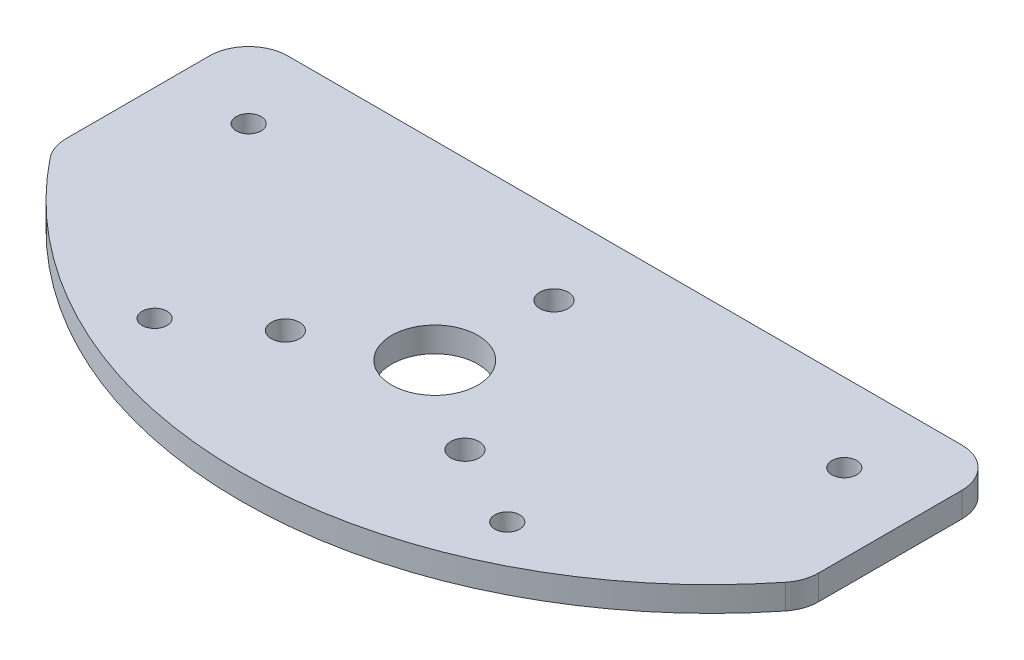
SolidWorks part; units mm, degrees
other "Markup1"
sketch "Sketch11" plane through (96, 6.36, -96) normal (0.0924, 0.995, -0.0379) x (0.9957, -0.0926, -0.0033)
ref_plane "Front Plane" through (0, 0, 0) normal (0, 0, 1) x (1, 0, 0)
ref_plane "Top Plane" through (0, 0, 0) normal (0, 1, 0) x (1, 0, 0)
ref_plane "Right Plane" through (0, 0, 0) normal (1, 0, 0) x (0, 0, -1)
sketch "Construction geometry" plane through (0, 0, 0) normal (0, 1, 0) x (1, 0, 0)
  line L1 (-96, 96) -> (96, 96)
  line L2 (-96, 96) -> (-96, -96)
  line L3 (-96, -96) -> (96, -96)
  line L4 (96, 96) -> (96, -96)
  line L5 (0, 96) -> (0, -96)
  line L6 (-96, 0) -> (96, 0)
  point P8 (0, 0)
  dimension "D1" = 192
  dimension "D2" = 192
sketch "Sketch5" plane through (0, 0, 0) normal (0, 1, 0) x (1, 0, 0)
  line L0 (-96, 0) -> (96, 0) construction
  line L1 (0, 96) -> (0, -96) construction
  circle A0 centre (0, 0) radius 38.5
  dimension "D1" = 77
extrude "Boss-Extrude2" add sketch "Sketch5" along normal blind 6.36
sketch "Sketch7" plane through (0, 6.36, 0) normal (0, 1, 0) x (1, 0, 0)
  line L0 (0, 96) -> (0, -96) construction
  line L1 (-96, 0) -> (96, 0) construction
  circle A0 centre (0, 0) radius 30 construction
  circle A1 centre (0, 30) radius 3.625
  circle A6 centre (25.9808, -15) radius 3.625
  circle A7 centre (-25.9808, -15) radius 3.625
  point P24 (0, 0)
  dimension "D2" = 60
  dimension "D1" = 7.25
  dimension "D4" = 3
extrude "Cut-Extrude3" [suppressed] cut sketch "Sketch7" against normal through all
sketch "Sketch8" plane through (0, 6.36, 0) normal (0, 1, 0) x (1, 0, 0)
  line L1 (-96, 0) -> (96, 0) construction
  circle A0 centre (0, 0) radius 11
  dimension "D1" = 22
extrude "Cut-Extrude4" cut sketch "Sketch8" against normal through all
sketch "Sketch9" plane through (0, 6.36, 0) normal (0, 1, 0) x (1, 0, 0)
  line L5 (-96, 48.5) -> (96, 48.5)
  line L6 (-96, 96) -> (-96, -96) construction
  line L7 (96, 96) -> (96, -96) construction
  line L8 (96, 48.5) -> (96, -1.5)
  line L9 (-96, 48.5) -> (-96, -1.5)
  line L10 (0, 96) -> (0, -96) construction
  circle A0 centre (0, 0) radius 38.5
  circle A3 centre (0, 0) radius 38.5 construction
  arc A4 (96, -1.5) -> (-96, -1.5) centre (0, 70.5) cw
  point P13 (0, -49.5)
  dimension "D1" = 120
  dimension "D2" = 50
  dimension "D3" = 10
extrude "Boss-Extrude3" add sketch "Sketch9" against normal up to surface (6.36 mm away) up to face at (0, 0, 11)
sketch "Sketch10" plane through (0, 6.36, 0) normal (0, 1, 0) x (1, 0, 0)
  line L0 (0, 48.5) -> (0, -49.5) construction
  line L1 (96, 48.5) -> (-96, 48.5) construction
  line L2 (-96, 48.5) -> (-96, -1.5) construction
  circle A0 centre (-76, 28.5) radius 3.175
  circle A2 centre (-45, -26.5) radius 3.175
  arc A3 (-96, -1.5) -> (96, -1.5) centre (0, 70.5) ccw construction
  circle A4 centre (45, -26.5) radius 3.175
  circle A5 centre (76, 28.5) radius 3.175
  dimension "D1" = 6.35
  dimension "D2" = 20
  dimension "D3" = 20
  dimension "D4" = 45
  dimension "D5" = 75
extrude "Cut-Extrude5" cut sketch "Sketch10" against normal through all
sketch "Sketch12" plane through (0, 6.36, 0) normal (0, 1, 0) x (1, 0, 0)
  line L0 (0, 0) -> (0, 48.5) construction
  line L1 (96, 48.5) -> (-96, 48.5) construction
  line L2 (0, 0) -> (1.9881, 28.4306) construction
  circle A0 centre (1.9881, 28.4306) radius 3.625
  circle A1 centre (23.6276, -15.937) radius 3.625
  circle A2 centre (-25.6156, -12.4936) radius 3.625
  point P14 (0, 0)
  dimension "D4" = 3
  dimension "D2" = 7.25
  dimension "D1" = 4
extrude "Cut-Extrude6" cut sketch "Sketch12" against normal through all
fillet "Fillet1" radius 10 4 edges at (96, 3.18, -48.5) (96, 3.18, 1.5) (-96, 3.18, 1.5) (-96, 3.18, -48.5)
equation "\"mount bolt size\"= 7.25mm"
equation "\"wire hole\"= 22mm"
equation "\"D1@Sketch7\"=\"mount bolt size\""
equation "\"D1@Sketch8\"=\"wire hole\""
equation "\"D2@Sketch12\"=\"mount bolt size\""
equation "\"Tilt angle\"= 4deg"
equation "\"D1@Sketch12\"=\"Tilt angle\""
